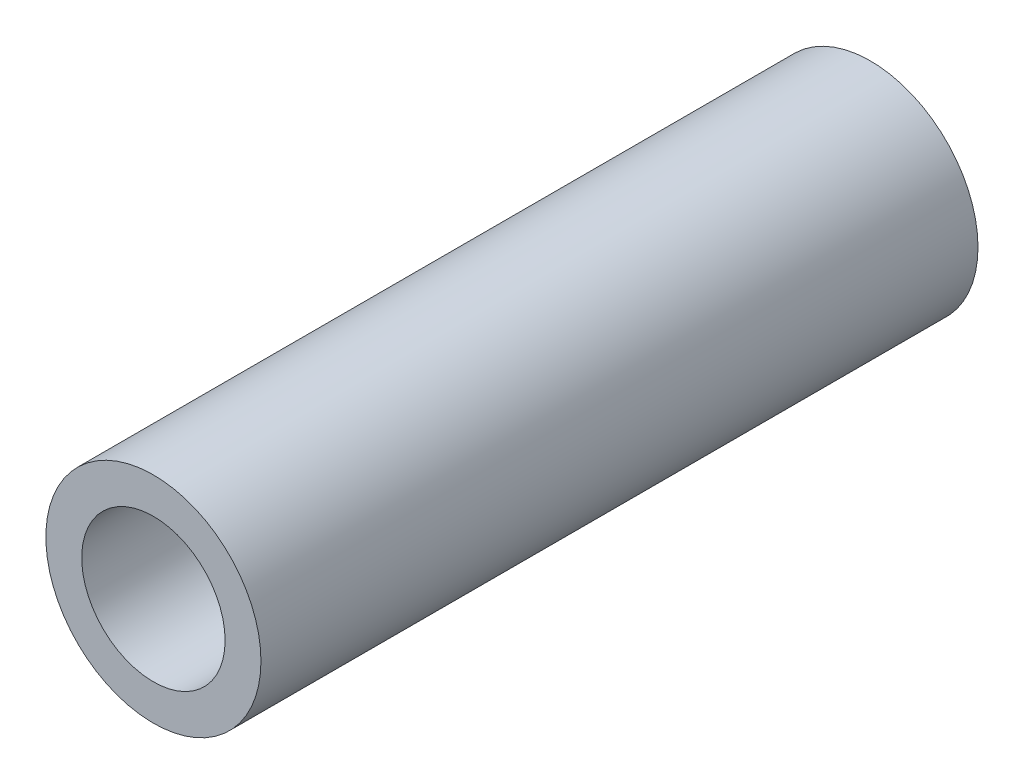
SolidWorks part; units mm, degrees
material "1.4000 (X6Cr13)"
ref_plane "正面" through (0, 0, 0) normal (0, 0, 1) x (1, 0, 0)
ref_plane "平面" through (0, 0, 0) normal (0, 1, 0) x (1, 0, 0)
ref_plane "右側面" through (0, 0, 0) normal (1, 0, 0) x (0, 0, -1)
sketch "ｽｹｯﾁ1" plane through (0, 0, 0) normal (0, 0, 1) x (1, 0, 0)
  circle A0 centre (0, 0) radius 3
  circle A1 centre (0, 0) radius 2
  dimension "D1" = 4
  dimension "D2" = 6
extrude "ﾎﾞｽ - 押し出し1" add sketch "ｽｹｯﾁ1" along normal blind 20
